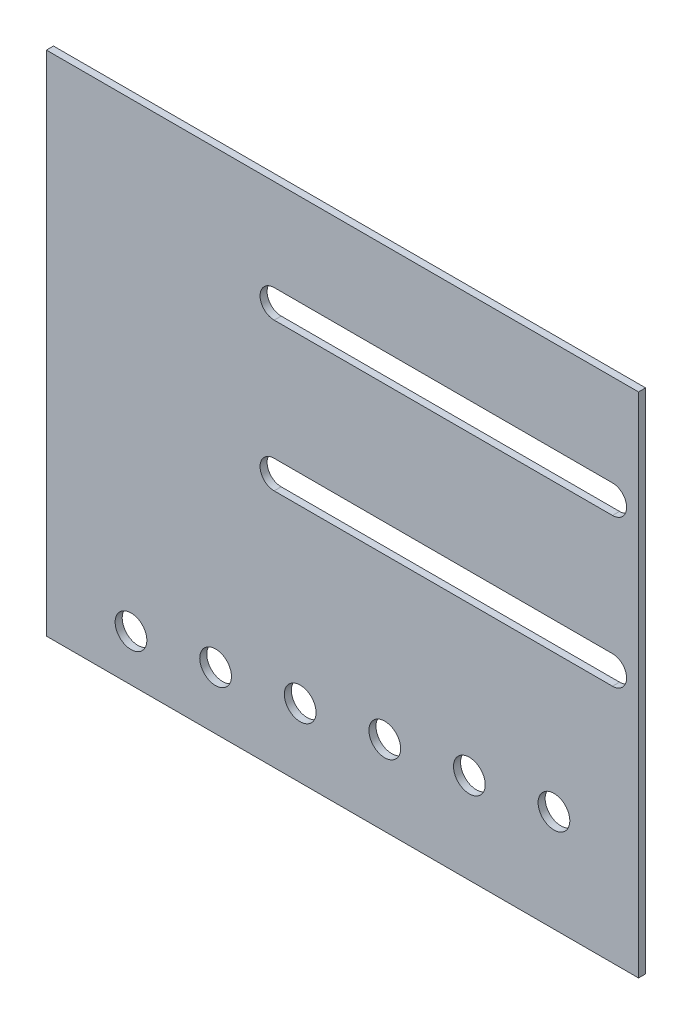
SolidWorks part; units mm, degrees
material "ABS PC"
ref_plane "Front Plane" through (0, 0, 0) normal (0, 0, 1) x (1, 0, 0)
ref_plane "Top Plane" through (0, 0, 0) normal (0, 1, 0) x (1, 0, 0)
ref_plane "Right Plane" through (0, 0, 0) normal (1, 0, 0) x (0, 0, -1)
sketch "Sketch1" plane through (0, 0, 0) normal (0, 0, 1) x (1, 0, 0)
  line L0 (0, -228.6) -> (0, 228.6) construction
  line L1 (-266.7, 228.6) -> (266.7, 228.6)
  line L2 (-266.7, 228.6) -> (-266.7, -228.6)
  line L3 (-266.7, -228.6) -> (266.7, -228.6)
  line L4 (266.7, 228.6) -> (266.7, -228.6)
  line L5 (-266.7, 228.6) -> (266.7, -228.6) construction
  line L6 (-266.7, -228.6) -> (266.7, 228.6) construction
  line L7 (-266.7, 0) -> (266.7, 0)
  line L8 (-266.7, 133.2022) -> (266.7, 133.2022) construction
  line L9 (-61.548, 133.2022) -> (243.252, 133.2022)
  line L10 (-61.548, 133.2022) -> (243.252, 133.2022) construction
  line L11 (-61.548, 145.9022) -> (243.252, 145.9022)
  line L12 (-61.548, 120.5022) -> (243.252, 120.5022)
  line L13 (-61.548, 133.2022) -> (-61.548, 0) construction
  line L14 (-61.548, 0) -> (243.252, 0) construction
  line L15 (-61.548, 0) -> (243.252, 0) construction
  line L16 (-61.548, 12.7) -> (243.252, 12.7)
  line L17 (-61.548, -12.7) -> (243.252, -12.7)
  arc A0 (-61.548, 145.9022) -> (-61.548, 120.5022) centre (-61.548, 133.2022) ccw
  arc A1 (243.252, 120.5022) -> (243.252, 145.9022) centre (243.252, 133.2022) ccw
  arc A2 (-61.548, 12.7) -> (-61.548, -12.7) centre (-61.548, 0) ccw
  arc A3 (243.252, -12.7) -> (243.252, 12.7) centre (243.252, 0) ccw
  point P0 (0, 0)
  point P12 (90.852, 133.2022)
  point P15 (90.852, 133.2022)
  point P22 (90.852, 0)
  dimension "D1" = 457.2
  dimension "D2" = 533.4
  dimension "D3" = 304.8
extrude "Boss-Extrude4" add sketch "Sketch1" along normal blind 6.35 contours L2 L1 L4 L3 | L12 A1 L11 A0 | L17 A3 L16 A2
sketch "Sketch3" plane through (0, 0, 0) normal (0, 0, -1) x (-1, 0, 0)
  line L0 (-266.7, -228.6) -> (-266.7, -127) construction
  line L1 (-266.7, -228.6) -> (-266.7, 228.6) construction
  line L2 (-266.7, -127) -> (266.7, -196.6093) construction
  line L3 (266.7, 228.6) -> (266.7, -228.6) construction
  line L4 (-266.7, -228.6) -> (-190.5, -228.6) construction
  line L5 (-190.5, -228.6) -> (-114.3, -228.6) construction
  line L6 (266.7, -228.6) -> (-266.7, -228.6) construction
  line L7 (-114.3, -228.6) -> (-38.1, -228.6) construction
  line L8 (-38.1, -228.6) -> (38.1, -228.6) construction
  line L9 (38.1, -228.6) -> (114.3, -228.6) construction
  line L10 (114.3, -228.6) -> (190.5, -228.6) construction
  line L11 (190.5, -228.6) -> (266.7, -228.6) construction
  circle A0 centre (-190.5, -136.9442) radius 14.2875
  circle A1 centre (-114.3, -146.8884) radius 14.2875
  circle A2 centre (-38.1, -156.8326) radius 14.2875
  circle A3 centre (38.1, -166.7767) radius 14.2875
  circle A4 centre (114.3, -176.7209) radius 14.2875
  circle A5 centre (190.5, -186.6651) radius 14.2875
  dimension "D8" = 28.575
  dimension "D9" = 28.575
  dimension "D10" = 28.575
  dimension "D11" = 28.575
  dimension "D12" = 28.575
  dimension "D13" = 28.575
  dimension "D1" = 101.6
  dimension "D2" = 76.2
  dimension "D3" = 76.2
  dimension "D4" = 76.2
  dimension "D5" = 76.2
  dimension "D6" = 76.2
  dimension "D7" = 76.2
extrude "Cut-Extrude2" cut sketch "Sketch3" against normal blind 12.7
